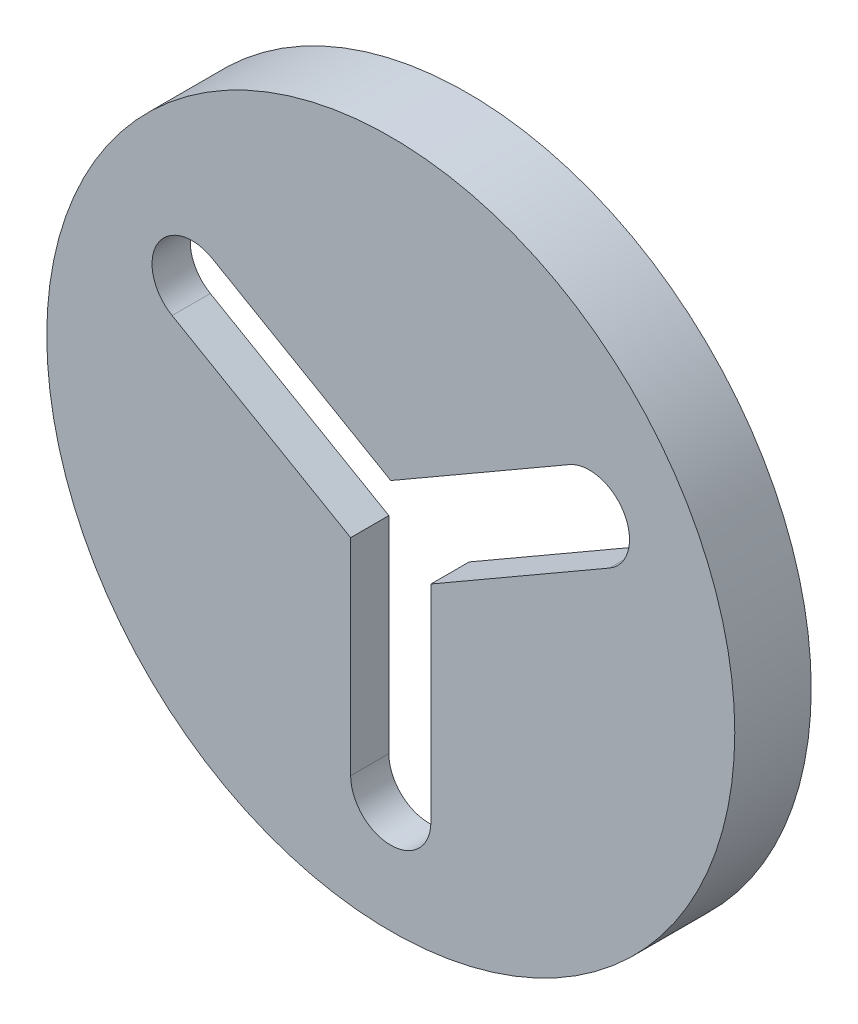
SolidWorks part; units mm, degrees
ref_plane "Alzado" through (0, 0, 0) normal (0, 0, 1) x (1, 0, 0)
ref_plane "Planta" through (0, 0, 0) normal (0, 1, 0) x (1, 0, 0)
ref_plane "Vista lateral" through (0, 0, 0) normal (1, 0, 0) x (0, 0, -1)
sketch "Croquis1" plane through (0, 0, 0) normal (0, 0, 1) x (1, 0, 0)
  circle A0 centre (0, 0) radius 40
  dimension "D1" = 80
extrude "Disco" add sketch "Croquis1" along normal blind 5
sketch "Croquis6" plane through (0, 0, 5) normal (0, 0, 1) x (1, 0, 0)
  line L0 (-5.25, 0) -> (-5.25, -30)
  line L1 (5.25, 0) -> (5.25, -30)
  line L2 (2.625, 4.5466) -> (-23.3558, 19.5466)
  line L3 (-2.625, -4.5466) -> (-28.6058, 10.4534)
  line L4 (2.625, -4.5466) -> (28.6058, 10.4534)
  line L5 (-2.625, 4.5466) -> (23.3558, 19.5466)
  arc A1 (-5.25, 0) -> (5.25, 0) centre (0, 0) cw
  arc A2 (-5.25, -30) -> (5.25, -30) centre (0, -30) ccw
  arc A3 (2.625, 4.5466) -> (-2.625, -4.5466) centre (0, 0) cw
  arc A4 (-23.3558, 19.5466) -> (-28.6058, 10.4534) centre (-25.9808, 15) ccw
  arc A5 (2.625, -4.5466) -> (-2.625, 4.5466) centre (0, 0) cw
  arc A6 (28.6058, 10.4534) -> (23.3558, 19.5466) centre (25.9808, 15) ccw
  point P22 (0, 0)
  dimension "D1" = 30
  dimension "D3" = 5.25
  dimension "D2" = 3
extrude "Cortar-Extruir1" cut sketch "Croquis6" against normal blind 10 contours L2 A4 L3 A3 | L5 A6 L4 A5 | L1 A2 L0 A1
sketch "Croquis7" plane through (0, 0, 5) normal (0, 0, 1) x (1, 0, 0)
  circle A0 centre (0, 0) radius 40
  circle A1 centre (0, 0) radius 45
  circle A2 centre (0, 0) radius 40
  circle M3 centre (0, 0) radius 40
  dimension "D1" = 90
  dimension "D2" = 80
extrude "Saliente-Extruir5" add sketch "Croquis7" against normal blind 10 contours A1 M3
sketch "Croquis8" plane through (0, 0, -5) normal (0, 0, -1) x (-1, 0, 0)
  circle A0 centre (0, 0) radius 41
  dimension "D1" = 82
extrude "Cortar-Extruir2" cut sketch "Croquis8" against normal blind 5
